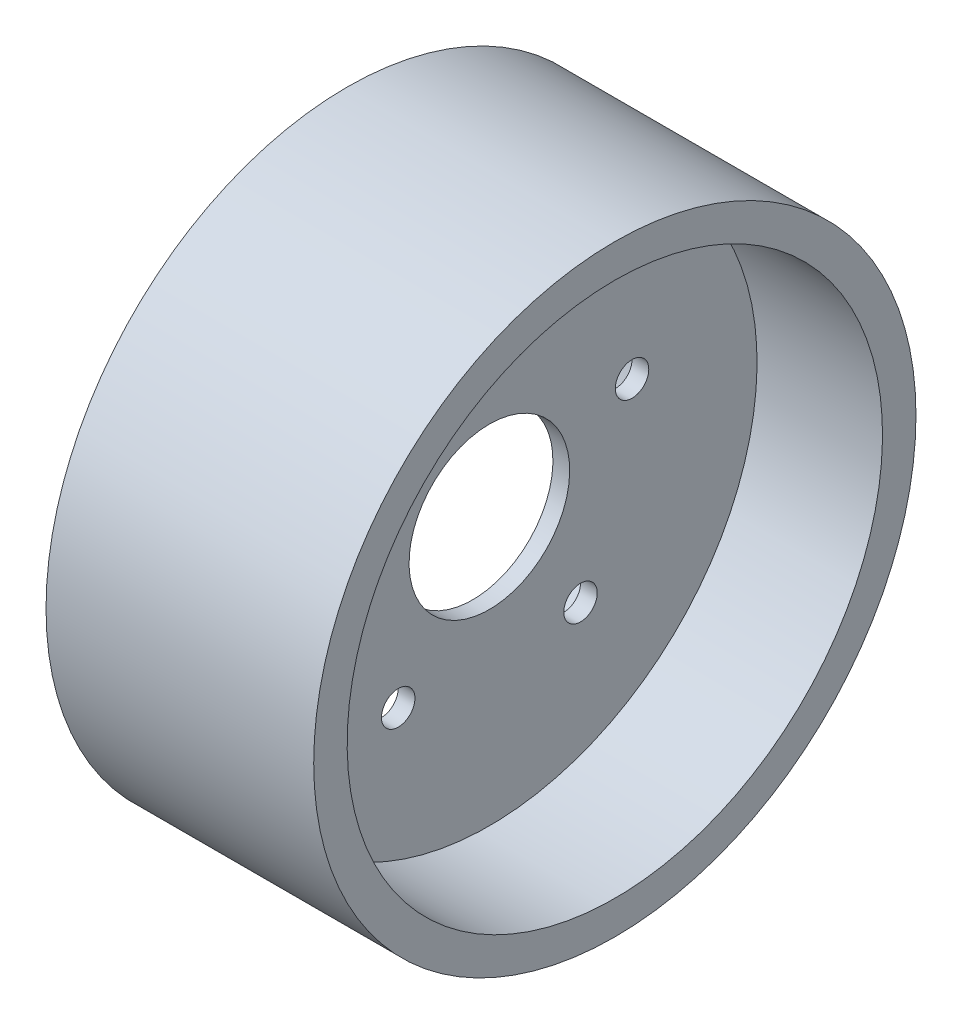
SolidWorks part; units mm, degrees
material "1060 Alloy"
ref_plane "Front Plane" through (0, 0, 0) normal (0, 0, 1) x (1, 0, 0)
ref_plane "Top Plane" through (0, 0, 0) normal (0, 1, 0) x (1, 0, 0)
ref_plane "Right Plane" through (0, 0, 0) normal (1, 0, 0) x (0, 0, -1)
sketch "Sketch1" plane through (0, 0, 0) normal (0, 0, 1) x (1, 0, 0)
  line L0 (0, 0) -> (0, 101.6)
  line L1 (0, 101.6) -> (6.35, 101.6)
  line L2 (6.35, 101.6) -> (6.35, 0)
  line L3 (6.35, 0) -> (0, 0)
  line L5 (-47.625, 114.3) -> (53.975, 114.3)
  line L6 (-47.625, 114.3) -> (-47.625, 101.6)
  line L7 (-47.625, 101.6) -> (53.975, 101.6)
  line L8 (53.975, 114.3) -> (53.975, 101.6)
  point P9 (3.175, 101.6)
  point P10 (3.175, 101.6)
  dimension "D1" = 101.6
  dimension "D2" = 6.35
  dimension "D3" = 101.6
  dimension ".5" = 12.7
revolve "Revolve1" add sketch "Sketch1" angle 360 about L3
sketch "Sketch2" plane through (6.35, 0, 0) normal (1, 0, 0) x (0, 0, -1)
  line L0 (0, 57.15) -> (-54.1556, 18.2562) construction
  line L1 (-54.1556, 18.2562) -> (-34.5994, -45.4863) construction
  line L2 (54.1556, 18.2562) -> (34.5994, -45.4863) construction
  line L3 (34.5994, -45.4863) -> (-34.5994, -45.4863) construction
  line L4 (0, 57.15) -> (54.1556, 18.2562) construction
  circle A0 centre (0, 0) radius 57.15
  circle A1 centre (0, 0) radius 30.48
  point P3 (0, 57.15)
  point P4 (34.5994, -45.4863)
  point P5 (54.1556, 18.2562)
  point P6 (-34.5994, -45.4863)
  point P7 (-54.1556, 18.2562)
  dimension "D1" = 114.3
  dimension "D3" = 60.96
  dimension "D2" = 66.675
extrude "Cut-Extrude2" cut sketch "Sketch2" against normal through all contours A1
hole_wizard "1/2 (0.5) Diameter Hole2" positions "Sketch5" profile "Sketch6" hole size "1/2" standard "ANSI Inch" end condition through all
sketch "Sketch5" plane through (6.35, 0, 0) normal (1, 0, 0) x (0, 0, -1)
  point P0 (-54.1556, 18.2562)
  point P3 (0, 57.15)
  point P6 (54.1556, 18.2562)
  point P9 (34.5994, -45.4863)
  point P12 (-34.5994, -45.4863)
sketch "Sketch6" plane through (6.35, 18.2562, 54.1556) normal (0, 1, 0) x (0, 0, -1)
  line L0 (0, 0) -> (0, 53.975)
  line L1 (0, 53.975) -> (6.35, 53.975)
  line L2 (6.35, 53.975) -> (6.35, 0)
  line L5 (6.35, 0) -> (0, 0)
  line L11 (0, -6.35) -> (0, 107.95) construction
  dimension "Thru Hole Dia." = 12.7
  dimension "Thru Hole Depth" = 53.975
